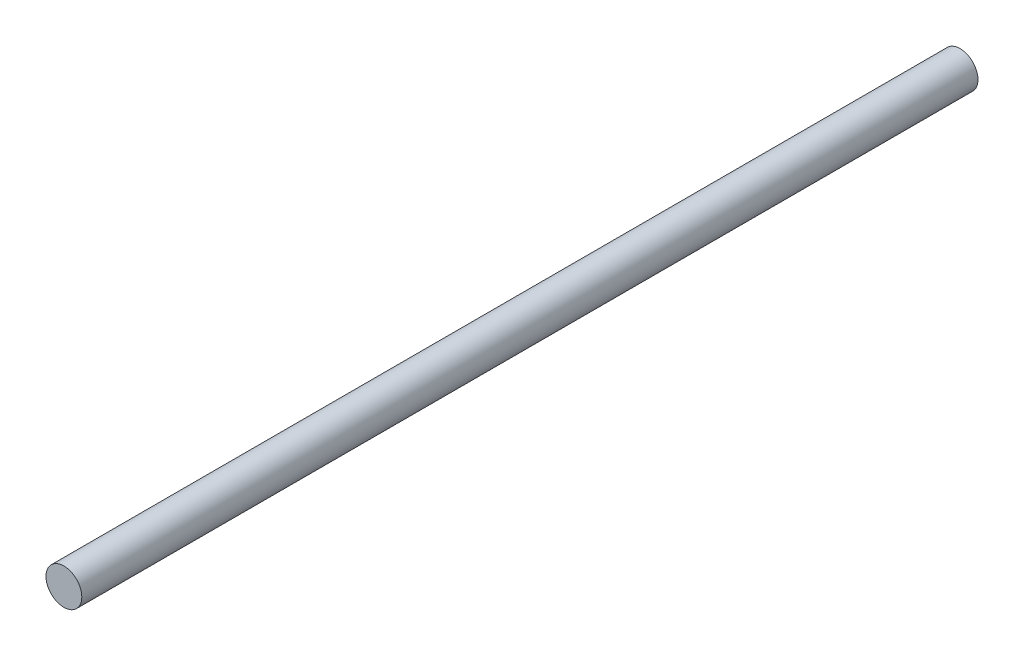
SolidWorks part; units mm, degrees
ref_plane "Front Plane" through (0, 0, 0) normal (0, 0, 1) x (1, 0, 0)
ref_plane "Top Plane" through (0, 0, 0) normal (0, 1, 0) x (1, 0, 0)
ref_plane "Right Plane" through (0, 0, 0) normal (1, 0, 0) x (0, 0, -1)
sketch "Sketch1" plane through (0, 0, 0) normal (0, 0, 1) x (1, 0, 0)
  circle A0 centre (0, 0) radius 8
  dimension "D1" = 16
extrude "Boss-Extrude2" add sketch "Sketch1" along normal blind 400
